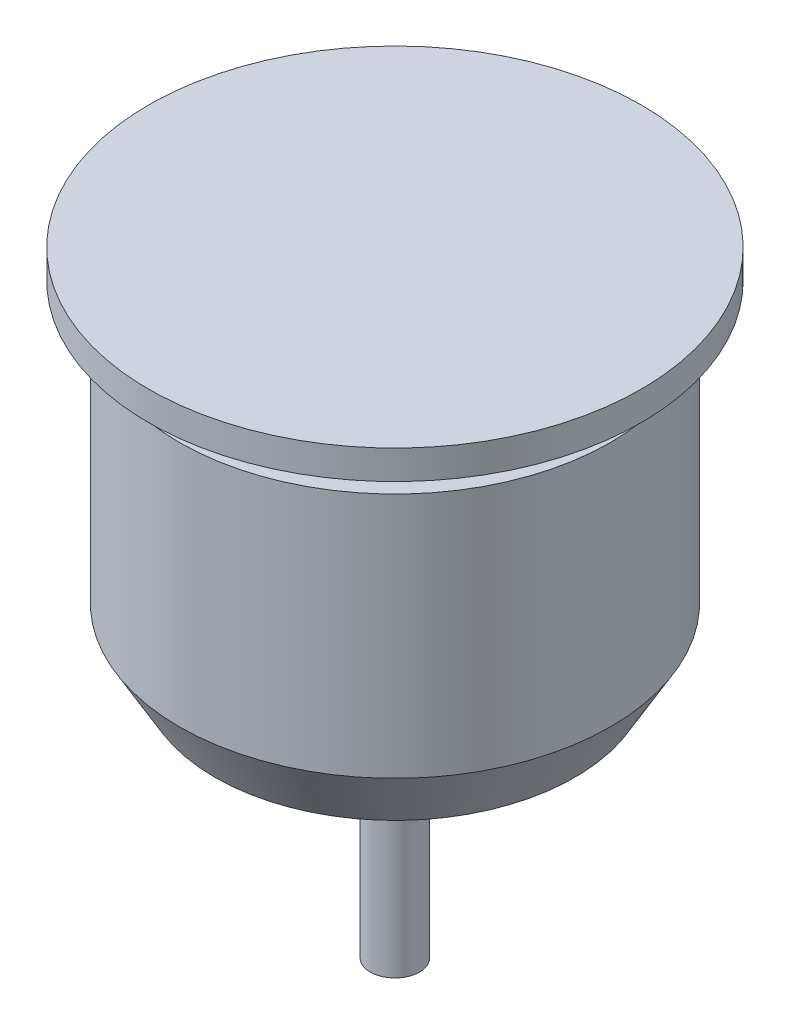
SolidWorks part; units mm, degrees
ref_plane "Přední rovina" through (0, 0, 0) normal (0, 0, 1) x (1, 0, 0)
ref_plane "Horní rovina" through (0, 0, 0) normal (0, 1, 0) x (1, 0, 0)
ref_plane "Pravá rovina" through (0, 0, 0) normal (1, 0, 0) x (0, 0, -1)
sketch "Skica1" plane through (0, 0, 0) normal (0, 0, 1) x (1, 0, 0)
  line L0 (0, 0) -> (0, 101.137) construction
  line L1 (0, 0) -> (2, 0)
  line L2 (2, 0) -> (2, 20)
  line L3 (2, 20) -> (14.6132, 20)
  line L4 (14.6132, 20) -> (17.5, 25)
  line L5 (17.5, 25) -> (17.5, 45)
  line L6 (17.5, 45) -> (14.5, 45)
  line L7 (14.5, 45) -> (14.5, 29)
  line L8 (14.5, 29) -> (0, 29)
  line L9 (0, 29) -> (0, 0)
  dimension "D1" = 4
  dimension "D2" = 25
  dimension "D3" = 35
  dimension "D4" = 3
  dimension "D5" = 20
  dimension "D6" = 60
  dimension "D7" = 20
  dimension "D8" = 16
revolve "Rotovat1" add sketch "Skica1" angle 360 about L0
sketch "Skica2" plane through (0, 0, 0) normal (0, 0, 1) x (1, 0, 0)
  line L0 (0, 30.5767) -> (1.8997, 30.5767)
  line L1 (1.8997, 30.5767) -> (1.8997, 32.6481)
  line L2 (1.8997, 32.6481) -> (12.533, 32.6481)
  line L3 (12.533, 32.6481) -> (12.533, 45)
  line L4 (17.5, 45) -> (-17.5, 45) construction
  line L5 (12.533, 45) -> (1.8997, 45)
  line L6 (14.5, 45) -> (-14.5, 45) construction
  line L7 (1.8997, 45) -> (1.8997, 47.6432)
  line L8 (1.8997, 47.6432) -> (20, 47.6432)
  line L9 (20, 47.6432) -> (20, 50)
  line L10 (20, 50) -> (0, 50)
  line L11 (0, 0) -> (0, 55.0254) construction
  line L12 (0, 50) -> (0, 30.5767)
  line L13 (-14.6132, 20) -> (14.6132, 20) construction
  dimension "D1" = 40
  dimension "D2" = 30
revolve "Rotovat2" add sketch "Skica2" angle 360 about L11
